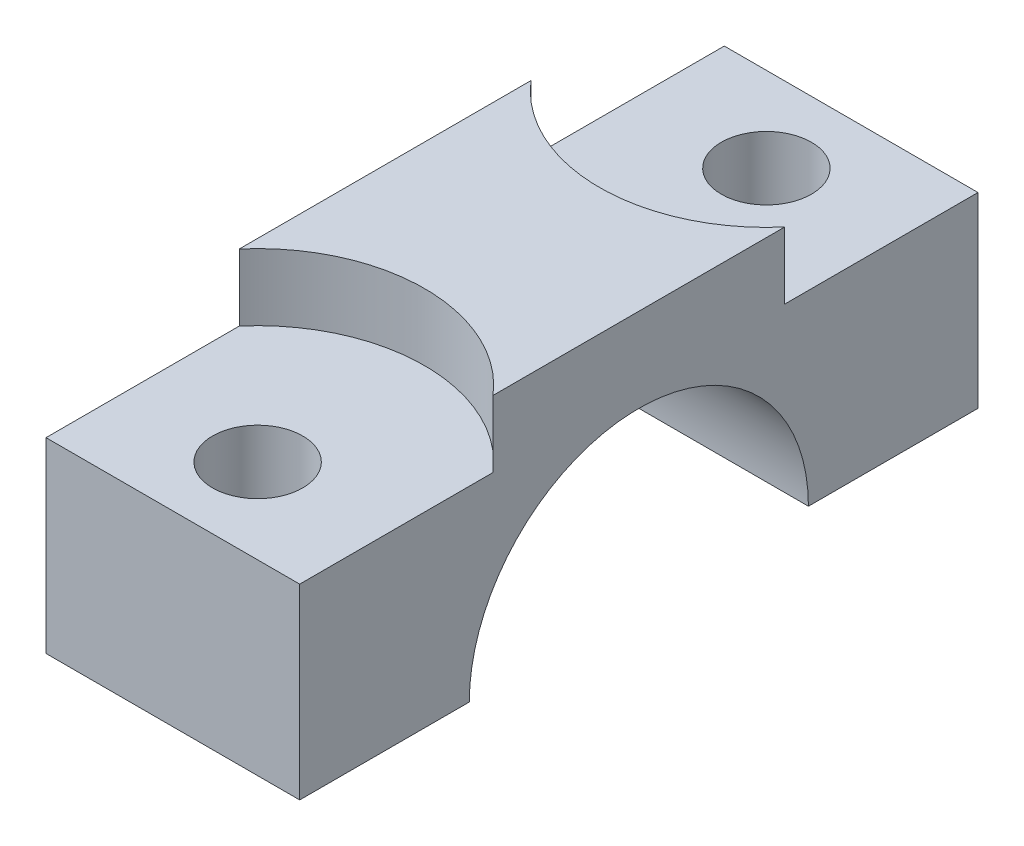
SolidWorks part; units mm, degrees
ref_plane "Front Plane" through (0, 0, 0) normal (0, 0, 1) x (1, 0, 0)
ref_plane "Top Plane" through (0, 0, 0) normal (0, 1, 0) x (1, 0, 0)
ref_plane "Right Plane" through (0, 0, 0) normal (1, 0, 0) x (0, 0, -1)
sketch "Sketch1" plane through (0, 0, 0) normal (1, 0, 0) x (0, 0, -1)
  line L0 (12.7, 0) -> (25.4, 0)
  line L1 (-25.4, 19) -> (25.4, 19)
  line L2 (-25.4, 19) -> (-25.4, 0)
  line L3 (-25.4, 0) -> (-12.7, 0)
  line L4 (25.4, 19) -> (25.4, 0)
  arc A0 (-12.7, 0) -> (12.7, 0) centre (0, 0) cw
  point P10 (0, 19)
  dimension "D1" = 50.8
  dimension "D3" = 12.7
  dimension "D2" = 19
extrude "Boss-Extrude1" add sketch "Sketch1" along normal mid plane 19
sketch "Sketch2" plane through (0, 0, 0) normal (0, -1, 0) x (1, 0, 0)
  line L0 (-9.5, 19.05) -> (9.5, 19.05) construction
  line L1 (-9.5, 25.4) -> (-9.5, 12.7) construction
  line L2 (9.5, 25.4) -> (9.5, 12.7) construction
  line L3 (-9.5, -19.05) -> (9.5, -19.05) construction
  line L4 (-9.5, -12.7) -> (-9.5, -25.4) construction
  line L5 (9.5, -12.7) -> (9.5, -25.4) construction
  point P12 (0, 19.05)
  point P13 (0, -19.05)
hole_wizard "CBORE for M12 Hex Head Cap Screw2" positions "Sketch4" profile "Sketch5" counterbore size "M12" standard "ISO" end condition through all
sketch "Sketch4" plane through (0, 19, 0) normal (0, 1, 0) x (1, 0, 0)
  point P0 (0, 19.05)
  point P3 (0, -19.05)
sketch "Sketch5" plane through (0, 19, -19.05) normal (1, 0, 0) x (0, 0, 1)
  line L0 (0, 0) -> (0, 19)
  line L1 (0, 19) -> (3.375, 19)
  line L3 (3.375, 19) -> (3.375, 5)
  line L4 (3.375, 5) -> (12.5, 5)
  line L5 (12.5, 5) -> (12.5, 0)
  line L7 (12.5, 0) -> (0, 0)
  line L11 (0, -6.35) -> (0, 107.95) construction
  dimension "Thru Hole Dia." = 6.75
  dimension "Thru Hole Depth" = 19
  dimension "C'Bore Dia." = 25
  dimension "C'Bore Depth" = 5
